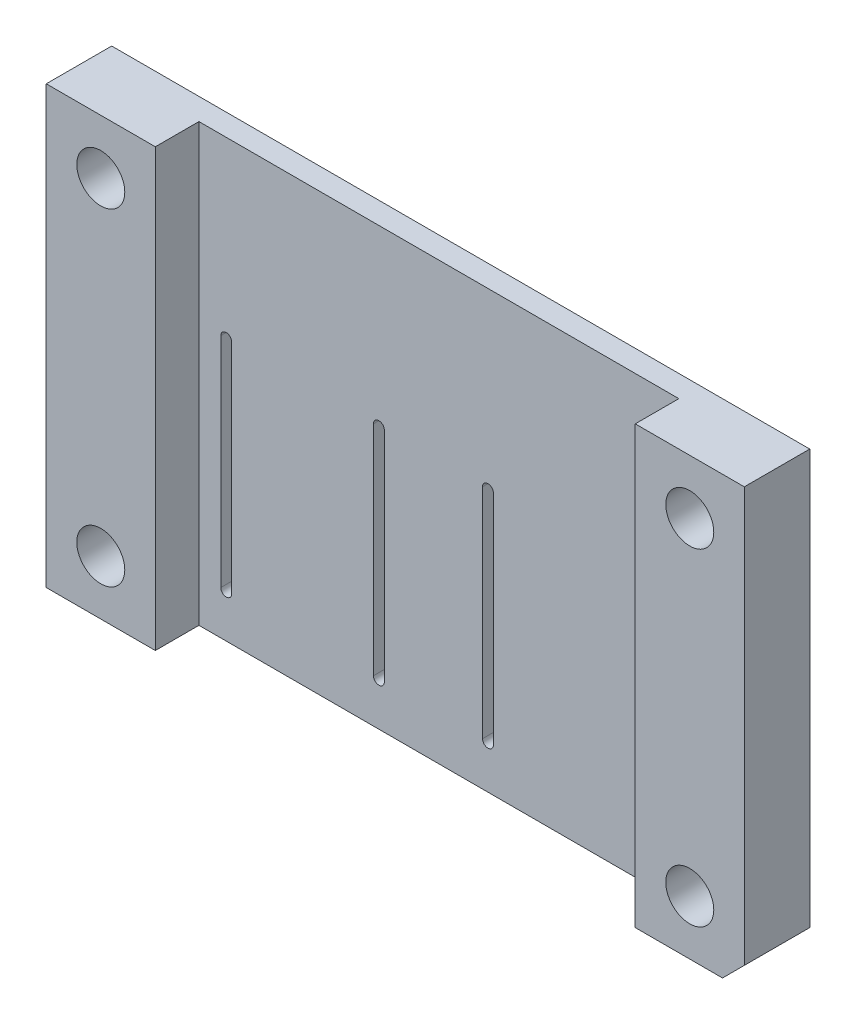
SolidWorks part; units mm, degrees
material "AISI 304"
ref_plane "Front" through (0, 0, 0) normal (0, 0, 1) x (1, 0, 0)
ref_plane "Top" through (0, 0, 0) normal (0, 1, 0) x (1, 0, 0)
ref_plane "Right" through (0, 0, 0) normal (1, 0, 0) x (0, 0, -1)
sketch "Sketch1" plane through (0, 0, 0) normal (0, 0, 1) x (1, 0, 0)
  line L1 (0, 0) -> (320, 0)
  line L2 (0, 0) -> (0, 200)
  line L3 (0, 200) -> (320, 200)
  line L4 (320, 0) -> (320, 200)
  line L5 (25, 175) -> (295, 175) construction
  line L6 (25, 175) -> (25, 25) construction
  line L7 (25, 25) -> (295, 25) construction
  line L8 (295, 175) -> (295, 25) construction
  circle A0 centre (25, 175) radius 11
  circle A1 centre (295, 175) radius 11
  circle A2 centre (25, 25) radius 11
  circle A3 centre (295, 25) radius 11
  dimension "D3" = 22
  dimension "D1" = 200
  dimension "D2" = 320
  dimension "D4" = 25
  dimension "D5" = 25
  dimension "D6" = 25
  dimension "D7" = 25
extrude "Boss-Extrude1" add sketch "Sketch1" along normal blind 30
cosmetic thread "Cosmetic Thread1" parameters "D2"=25
cosmetic thread "Cosmetic Thread2" parameters "D2"=25
cosmetic thread "Cosmetic Thread3" parameters "D2"=25
cosmetic thread "Cosmetic Thread4" parameters "D2"=25
sketch "Sketch2" plane through (0, 0, 30) normal (0, 0, 1) x (1, 0, 0)
  line L0 (257.5, 120) -> (257.5, 20) construction
  line L1 (260, 120) -> (260, 20)
  line L2 (255, 120) -> (255, 20)
  line L4 (320, 200) -> (0, 200) construction
  line L5 (182.5, 120) -> (182.5, 20) construction
  line L6 (185, 120) -> (185, 20)
  line L7 (180, 120) -> (180, 20)
  line L8 (182.5, 120) -> (257.5, 120) construction
  line L9 (62.5, 120) -> (62.5, 20) construction
  line L10 (65, 120) -> (65, 20)
  line L11 (60, 120) -> (60, 20)
  line L12 (132.5, 120) -> (132.5, 20) construction
  line L13 (135, 120) -> (135, 20)
  line L14 (130, 120) -> (130, 20)
  line L15 (62.5, 120) -> (132.5, 120) construction
  line L16 (132.5, 120) -> (135, 120) construction
  line L17 (0, 0) -> (320, 0) construction
  arc A0 (260, 120) -> (255, 120) centre (257.5, 120) ccw
  arc A1 (255, 20) -> (260, 20) centre (257.5, 20) ccw
  arc A2 (185, 120) -> (180, 120) centre (182.5, 120) ccw
  arc A3 (180, 20) -> (185, 20) centre (182.5, 20) ccw
  arc A4 (65, 120) -> (60, 120) centre (62.5, 120) ccw
  arc A5 (60, 20) -> (65, 20) centre (62.5, 20) ccw
  arc A6 (135, 120) -> (130, 120) centre (132.5, 120) ccw
  arc A7 (130, 20) -> (135, 20) centre (132.5, 20) ccw
  circle A9 centre (295, 175) radius 11 construction
  point P2 (257.5, 70)
  point P13 (182.5, 70)
  point P22 (62.5, 70)
  point P27 (132.5, 70)
  dimension "D2" = 2.5
  dimension "D4" = 80
  dimension "D8" = 20
  dimension "D1" = 37.5
  dimension "D3" = 100
  dimension "D5" = 75
  dimension "D6" = 50
  dimension "D7" = 70
extrude "Cut-Extrude1" cut sketch "Sketch2" against normal through all
sketch "Sketch4" plane through (0, 0, 30) normal (0, 0, 1) x (1, 0, 0)
  line L0 (320, 200) -> (0, 200) construction
  line L1 (50, 200) -> (270, 200)
  line L2 (50, 200) -> (50, 0)
  line L3 (50, 0) -> (270, 0)
  line L4 (270, 200) -> (270, 0)
  line L5 (0, 0) -> (320, 0) construction
  line L6 (0, 200) -> (0, 0) construction
  line L7 (320, 0) -> (320, 200) construction
  dimension "D1" = 50
  dimension "D2" = 50
extrude "Cut-Extrude2" cut sketch "Sketch4" against normal blind 20
chamfer "Chamfer1" distance 10 angle 45 1 edges at (320, 0, 15)
